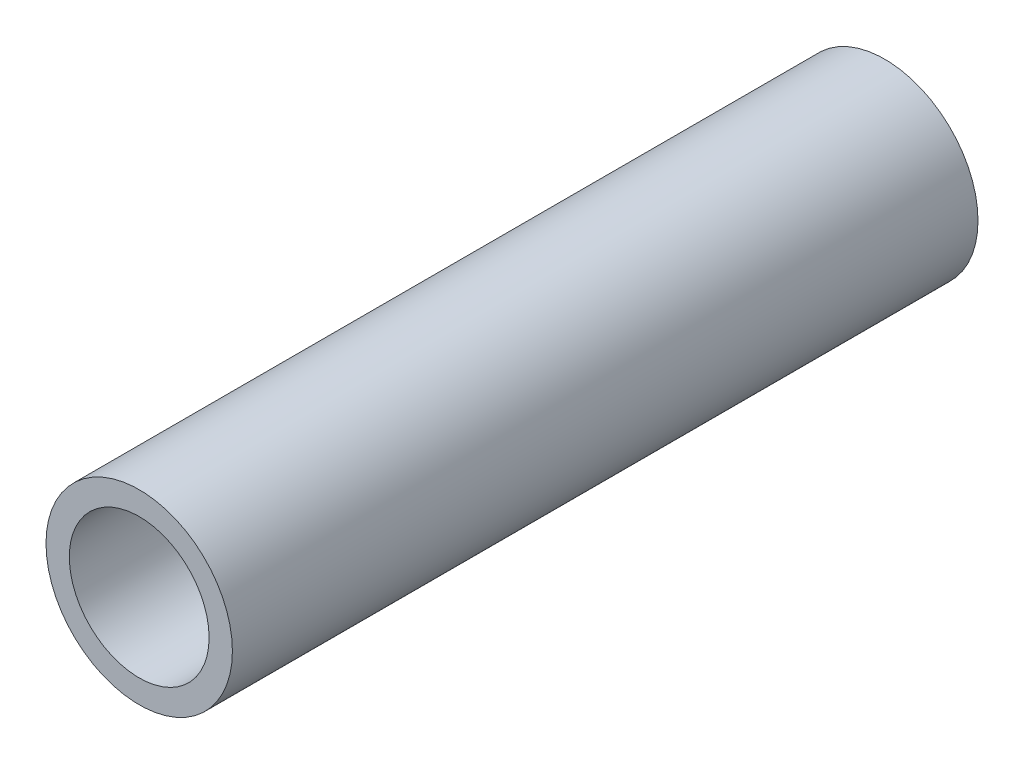
SolidWorks part; units mm, degrees
ref_plane "Front Plane" through (0, 0, 0) normal (0, 0, 1) x (1, 0, 0)
ref_plane "Top Plane" through (0, 0, 0) normal (0, 1, 0) x (1, 0, 0)
ref_plane "Right Plane" through (0, 0, 0) normal (1, 0, 0) x (0, 0, -1)
sketch "Sketch1" plane through (0, 0, 0) normal (0, 0, 1) x (1, 0, 0)
  circle A0 centre (0, 0) radius 20
  circle A1 centre (0, 0) radius 15
  dimension "D1" = 40
  dimension "D2" = 5
extrude "Boss-Extrude1" add sketch "Sketch1" along normal blind 160
